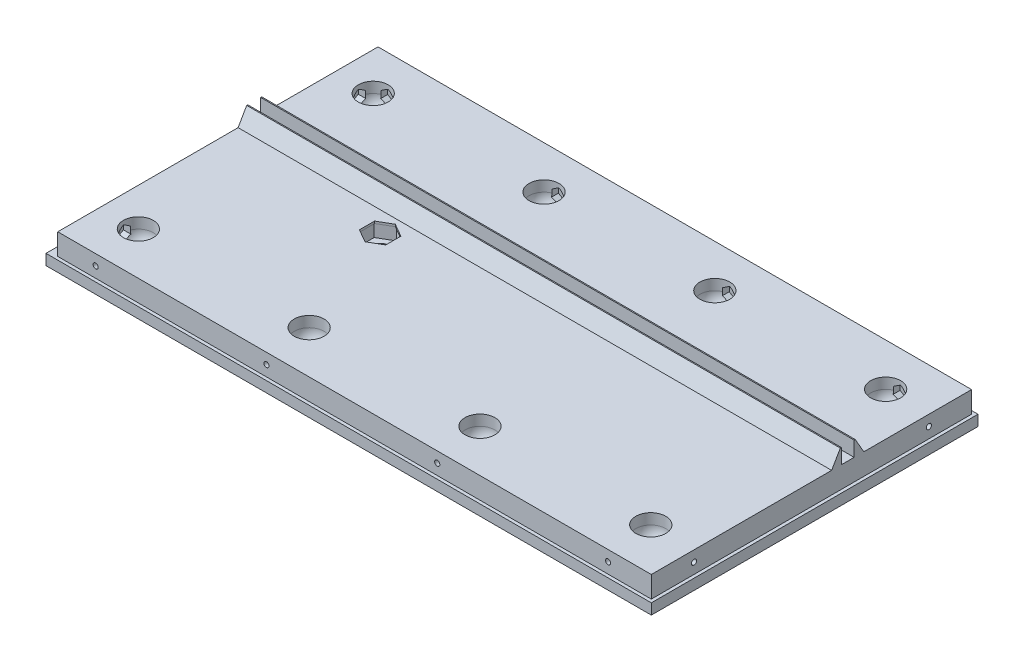
SolidWorks part; units mm, degrees
material "ABS"
ref_plane "Plan de face" through (0, 0, 0) normal (0, 0, 1) x (1, 0, 0)
ref_plane "Plan de dessus" through (0, 0, 0) normal (0, 1, 0) x (1, 0, 0)
ref_plane "Plan de droite" through (0, 0, 0) normal (1, 0, 0) x (0, 0, -1)
sketch "Esquisse1" plane through (0, 0, 0) normal (0, 1, 0) x (1, 0, 0)
  line L0 (-141.75, 0) -> (141.75, 0) construction
  line L1 (-141.75, 76.5) -> (141.75, 76.5)
  line L2 (-141.75, 76.5) -> (-141.75, -76.5)
  line L3 (-141.75, -76.5) -> (141.75, -76.5)
  line L4 (141.75, 76.5) -> (141.75, -76.5)
  dimension "D1" = 153
  dimension "D2" = 283.5
extrude "Boss.-Extru.1" add sketch "Esquisse1" along normal blind 15
sketch "Esquisse3" plane through (0, 0, 0) normal (0, -1, 0) x (1, 0, 0)
  line L1 (-141.75, 76.5) -> (141.75, 76.5)
  line L2 (-141.75, 76.5) -> (-141.75, -76.5)
  line L3 (-141.75, -76.5) -> (141.75, -76.5)
  line L4 (141.75, 76.5) -> (141.75, -76.5)
extrude "Enlèv. de mat.-Extru.-Mince1" cut sketch "Esquisse3" against normal through all from offset 5 thin offset against normal yes
sketch "Esquisse4" plane through (141.75, 0, 0) normal (1, 0, 0) x (0, 0, -1)
  line L0 (-76.5, 5) -> (-76.5, 0) construction
  line L1 (-76.5, 0) -> (76.5, 0) construction
  circle A0 centre (-55, 10) radius 1.2
  dimension "D1" = 2.4
  dimension "D2" = 10
  dimension "D3" = 55
  dimension "D4" = 21.5
extrude "Enlèv. mat.-Extru.1" cut sketch "Esquisse4" against normal blind 12
sketch "Esquisse5" plane through (129.75, 0, 0) normal (1, 0, 0) x (0, 0, -1)
  line L1 (-52.25, 11.5877) -> (-55, 13.1754)
  line L2 (-55, 13.1754) -> (-57.75, 11.5877)
  line L3 (-57.75, 11.5877) -> (-57.75, 8.4123)
  line L4 (-57.75, 8.4123) -> (-55, 6.8246)
  line L5 (-55, 6.8246) -> (-52.25, 8.4123)
  line L6 (-52.25, 8.4123) -> (-52.25, 11.5877)
  circle A0 centre (-55, 10) radius 2.75 construction
  dimension "D1" = 5.5
extrude "Enlèv. mat.-Extru.2" cut sketch "Esquisse5" against normal blind 3.5
sketch "Esquisse6" plane through (0, 0, 76.5) normal (0, 0, 1) x (1, 0, 0)
  line L0 (-141.75, 0) -> (141.75, 0) construction
  line L2 (141.75, 5) -> (141.75, 0) construction
  circle A0 centre (120, 10) radius 1.2
  dimension "D1" = 10
  dimension "D2" = 2.4
  dimension "D4" = 21.75
  dimension "D3" = 120
extrude "Enlèv. mat.-Extru.3" cut sketch "Esquisse6" against normal blind 12
sketch "Esquisse7" plane through (0, 0, 64.5) normal (0, 0, 1) x (1, 0, 0)
  line L1 (122.75, 11.5877) -> (120, 13.1754)
  line L2 (120, 13.1754) -> (117.25, 11.5877)
  line L3 (117.25, 11.5877) -> (117.25, 8.4123)
  line L4 (117.25, 8.4123) -> (120, 6.8246)
  line L5 (120, 6.8246) -> (122.75, 8.4123)
  line L6 (122.75, 8.4123) -> (122.75, 11.5877)
  circle A0 centre (120, 10) radius 2.75 construction
  dimension "D1" = 5.5
extrude "Enlèv. mat.-Extru.4" cut sketch "Esquisse7" against normal blind 3.5
ref_plane "Plan1" through (0, 0, 55) normal (0, 0, 1) x (1, 0, 0)
sketch "Esquisse9" plane through (0, 0, 55) normal (0, 0, 1) x (1, 0, 0)
  line L0 (120, 27) -> (120, 15) construction
  line L1 (140.25, 15) -> (-140.25, 15) construction
  line L2 (120, 15) -> (120, 3)
  line L3 (127, 10) -> (127, 15)
  line L4 (127, 15) -> (120, 15)
  arc A0 (120, 3) -> (127, 10) centre (120, 10) ccw
  circle A1 centre (120, 10) radius 1.2 construction
  dimension "D1" = 7
revolve "Enlèvement de matière-Révolution1" cut sketch "Esquisse9" angle 360 about L0
pattern_linear "Répétition linéaire1" count 4 spacing 80 along (-1, 0, 0) of "Enlèv. mat.-Extru.3", "Enlèv. mat.-Extru.4", "Enlèvement de matière-Révolution1"
mirror "Symétrie2" about plane through (0, 0, 0) normal (1, 0, 0) of "Enlèv. mat.-Extru.2", "Enlèv. mat.-Extru.1"
mirror "Symétrie1" about plane through (0, 0, 0) normal (0, 0, 1) of "Symétrie2", "Enlèv. mat.-Extru.1", "Enlèv. mat.-Extru.2", "Répétition linéaire1", "Enlèv. mat.-Extru.3", "Enlèv. mat.-Extru.4", "Enlèvement de matière-Révolution1"
sketch "Esquisse10" plane through (0, 0, 0) normal (0, -1, 0) x (1, 0, 0)
  line L0 (-141.75, 0) -> (-61.75, 0) construction
  line L1 (-141.75, -76.5) -> (-141.75, 76.5) construction
  circle A0 centre (-61.75, 0) radius 4
  dimension "D1" = 8
  dimension "D2" = 80
extrude "Enlèv. mat.-Extru.6" cut sketch "Esquisse10" against normal blind 8
sketch "Esquisse11" plane through (0, 8, 0) normal (0, -1, 0) x (1, 0, 0)
  line L1 (-55.2, 3.7816) -> (-61.75, 7.5633)
  line L2 (-61.75, 7.5633) -> (-68.3, 3.7816)
  line L3 (-68.3, 3.7816) -> (-68.3, -3.7816)
  line L4 (-68.3, -3.7816) -> (-61.75, -7.5633)
  line L5 (-61.75, -7.5633) -> (-55.2, -3.7816)
  line L6 (-55.2, -3.7816) -> (-55.2, 3.7816)
  circle A0 centre (-61.75, 0) radius 6.55 construction
  dimension "D1" = 13.1
extrude "Enlèv. mat.-Extru.7" cut sketch "Esquisse11" against normal through all
sketch "Esquisse12" plane through (0, 8, 0) normal (0, 1, 0) x (1, 0, 0)
  line L0 (-55.6, -3.5507) -> (-55.6, 3.5507)
  line L1 (-55.6, 3.5507) -> (-61.75, 7.1014)
  line L2 (-61.75, 7.1014) -> (-67.9, 3.5507)
  line L3 (-67.9, 3.5507) -> (-67.9, -3.5507)
  line L4 (-67.9, -3.5507) -> (-61.75, -7.1014)
  line L5 (-61.75, -7.1014) -> (-55.6, -3.5507)
  line L6 (-55.2, -3.7816) -> (-55.2, 3.7816)
  line L7 (-55.2, 3.7816) -> (-61.75, 7.5633)
  line L8 (-61.75, 7.5633) -> (-68.3, 3.7816)
  line L9 (-68.3, 3.7816) -> (-68.3, -3.7816)
  line L10 (-68.3, -3.7816) -> (-61.75, -7.5633)
  line L11 (-61.75, -7.5633) -> (-55.2, -3.7816)
  line L12 (-55.2, -3.7816) -> (-55.2, 3.7816)
  line L13 (-55.2, 3.7816) -> (-61.75, 7.5633)
  line L14 (-61.75, 7.5633) -> (-68.3, 3.7816)
  line L15 (-68.3, 3.7816) -> (-68.3, -3.7816)
  line L16 (-68.3, -3.7816) -> (-61.75, -7.5633)
  line L17 (-61.75, -7.5633) -> (-55.2, -3.7816)
  dimension "D1" = 0
  dimension "D2" = 0.4
extrude "Boss.-Extru.2" add sketch "Esquisse12" along normal up to surface (1 mm away) from offset 6 up to face at (-61.75, 15, 0)
sketch "Esquisse13" plane through (0, 0, 75) normal (0, 0, 1) x (1, 0, 0)
  line L0 (140.25, 15) -> (-140.25, 15) construction
  line L1 (-141.75, 5) -> (-137.75, 5)
  line L2 (-141.75, 5) -> (-141.75, 15)
  line L3 (-141.75, 15) -> (-137.75, 15)
  line L4 (-137.75, 5) -> (-137.75, 15)
  dimension "D1" = 4
extrude "Enlèv. mat.-Extru.8" cut sketch "Esquisse13" against normal through all
sketch "Esquisse14" plane through (140.25, 0, 0) normal (1, 0, 0) x (0, 0, -1)
  line L0 (75, 15) -> (-75, 15) construction
  line L1 (9.4585, 15) -> (14, 15)
  line L2 (9.4585, 15) -> (13.5, 22)
  line L3 (13.5, 22) -> (14, 22)
  line L4 (14, 15) -> (14, 22)
  line L5 (17, 15) -> (17, 22) construction
  line L6 (20, 15) -> (20, 22)
  line L7 (20.5, 22) -> (20, 22)
  line L8 (24.5415, 15) -> (20.5, 22)
  line L9 (24.5415, 15) -> (20, 15)
  dimension "D1" = 7
  dimension "D2" = 6
  dimension "D3" = 17
  dimension "D4" = 0.5
  dimension "D5" = 30
extrude "Boss.-Extru.3" add sketch "Esquisse14" against normal up to surface (278 mm away) up to face at (-137.75, 10, 0)
sketch "Esquisse15" plane through (0, 0, 0) normal (0, -1, 0) x (1, 0, 0)
  line L8 (-136.75, 71.5) -> (-136.75, -71.5)
  line L9 (-136.75, -71.5) -> (136.75, -71.5)
  line L10 (136.75, -71.5) -> (136.75, 71.5)
  line L11 (136.75, 71.5) -> (-136.75, 71.5)
  line L12 (-136.75, 71.5) -> (-136.75, -71.5)
  line L13 (-136.75, -71.5) -> (136.75, -71.5)
  line L14 (136.75, -71.5) -> (136.75, 71.5)
  line L15 (136.75, 71.5) -> (-136.75, 71.5)
  dimension "D1" = 5
extrude "Enlèv. mat.-Extru.9" [suppressed] cut sketch "Esquisse15" against normal through all draft 89
